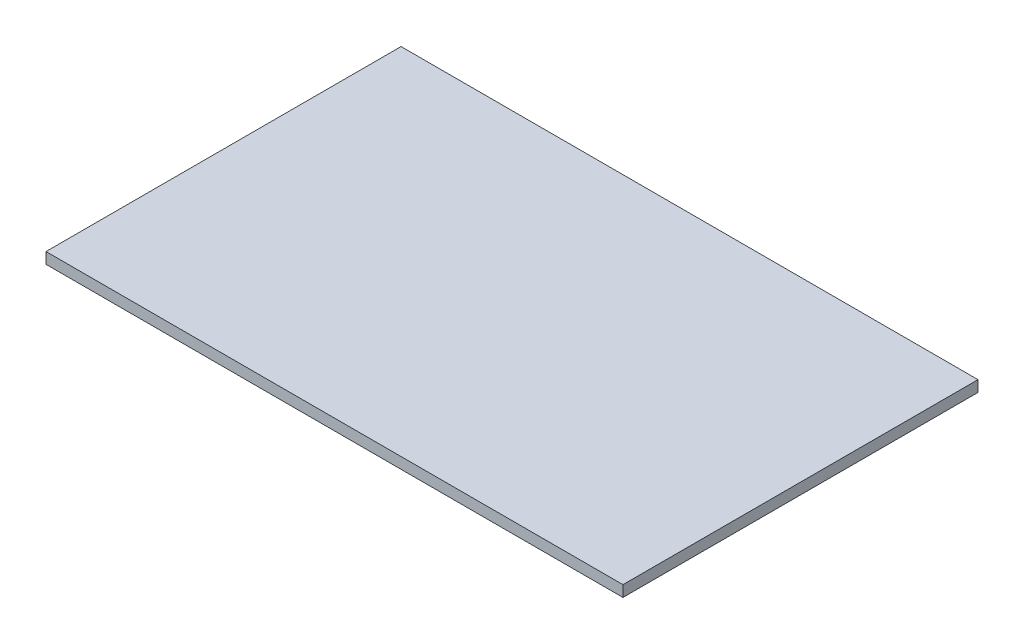
SolidWorks part; units mm, degrees
material "橡木"
ref_plane "前视基准面" through (0, 0, 0) normal (0, 0, 1) x (1, 0, 0)
ref_plane "上视基准面" through (0, 0, 0) normal (0, 1, 0) x (1, 0, 0)
ref_plane "右视基准面" through (0, 0, 0) normal (1, 0, 0) x (0, 0, -1)
sketch "草图1" plane through (0, 0, 0) normal (0, 1, 0) x (1, 0, 0)
  line L1 (-52, -32) -> (52, -32)
  line L2 (-52, -32) -> (-52, 32)
  line L3 (-52, 32) -> (52, 32)
  line L4 (52, -32) -> (52, 32)
  line L5 (-52, -32) -> (52, 32) construction
  line L6 (-52, 32) -> (52, -32) construction
  point P0 (0, 0)
  dimension "D1" = 64
  dimension "D2" = 104
extrude "凸台-拉伸1" add sketch "草图1" along normal blind 2
